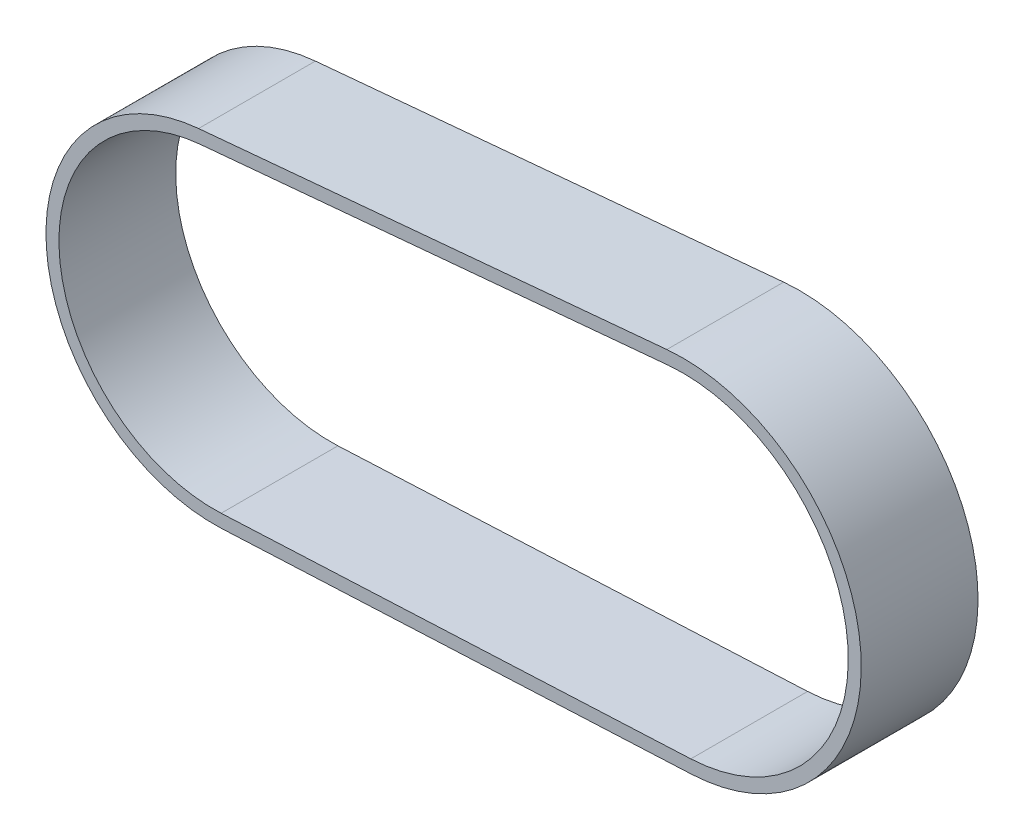
SolidWorks part; units mm, degrees
ref_plane "Front Plane" through (0, 0, 0) normal (0, 0, 1) x (1, 0, 0)
ref_plane "Top Plane" through (0, 0, 0) normal (0, 1, 0) x (1, 0, 0)
ref_plane "Right Plane" through (0, 0, 0) normal (1, 0, 0) x (0, 0, -1)
sketch "Sketch2" plane through (0, 0, 0) normal (0, 0, 1) x (1, 0, 0)
  line L0 (0, 0) -> (1, 0) construction
  line L1 (0, 0) -> (0, 1) construction
  line L2 (-1.0847, 11.8872) -> (34.9979, 15.1797)
  line L3 (36.7541, -10.2183) -> (0.5617, -11.9234)
  arc A0 (0.5617, -11.9234) -> (-1.0847, 11.8872) centre (0, 0) cw
  arc A1 (34.9979, 15.1797) -> (36.7541, -10.2183) centre (36.1549, 2.5) cw
extrude "Extrude-Thin1" add sketch "Sketch2" along normal blind 9 thin thin type one direction wall 1
